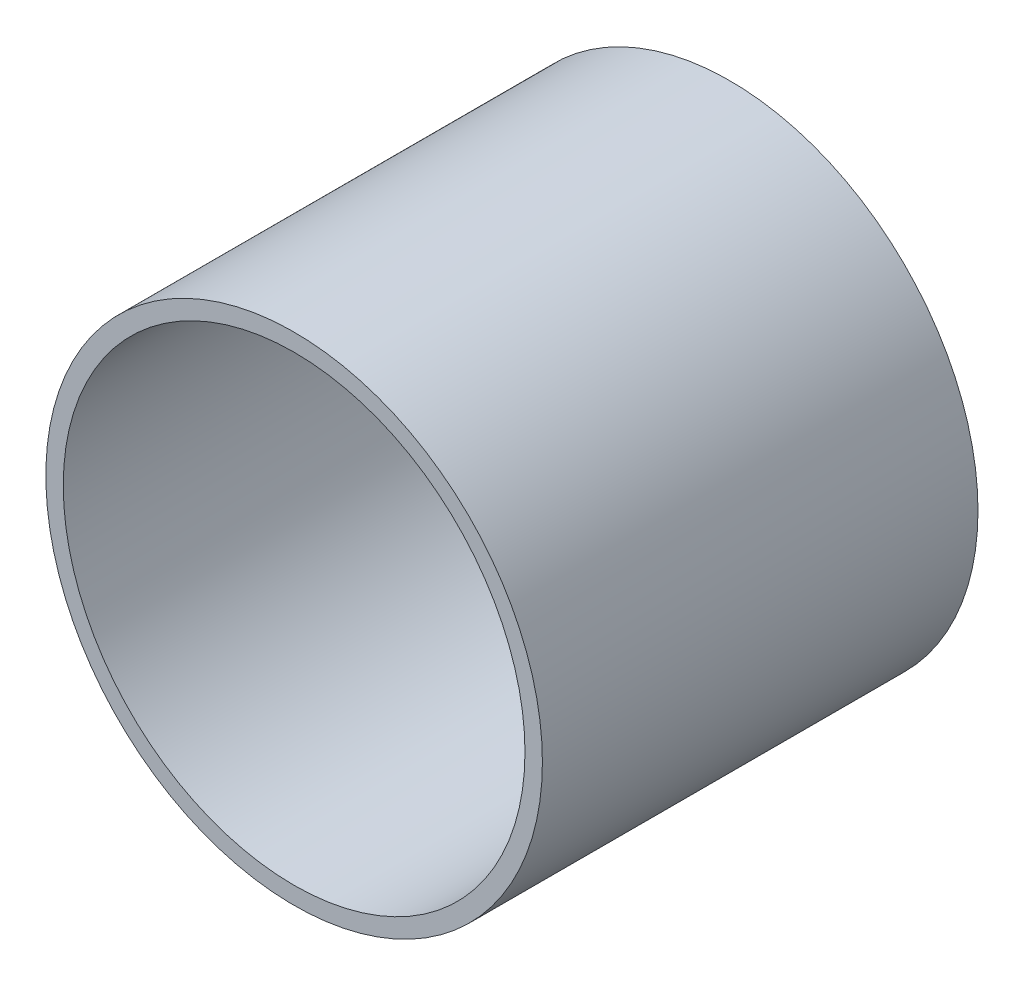
SolidWorks part; units mm, degrees
ref_plane "Front Plane" through (0, 0, 0) normal (0, 0, 1) x (1, 0, 0)
ref_plane "Top Plane" through (0, 0, 0) normal (0, 1, 0) x (1, 0, 0)
ref_plane "Right Plane" through (0, 0, 0) normal (1, 0, 0) x (0, 0, -1)
sketch "Sketch1" plane through (0, 0, 0) normal (0, 0, 1) x (1, 0, 0)
  circle A0 centre (0, 0) radius 285
extrude "Boss-Extrude2" add sketch "Sketch1" along normal blind 500
sketch "Sketch2" plane through (0, 0, 500) normal (0, 0, 1) x (1, 0, 0)
  circle A0 centre (0, 0) radius 265
extrude "Cut-Extrude1" cut sketch "Sketch2" against normal blind 499
